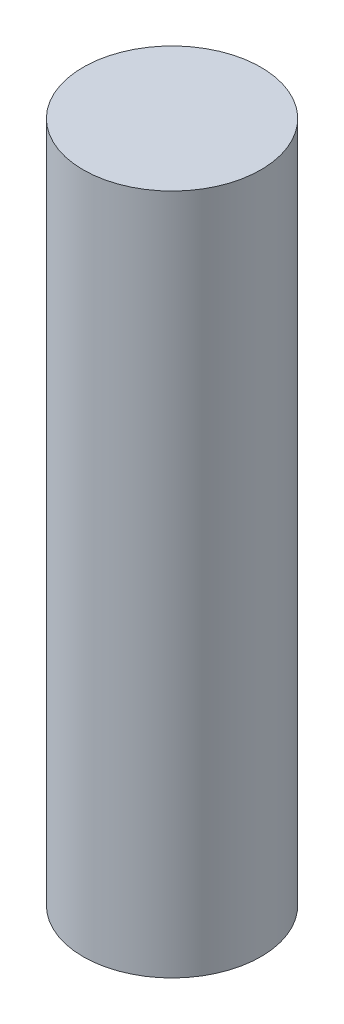
SolidWorks part; units mm, degrees
ref_plane "Front Plane" through (0, 0, 0) normal (0, 0, 1) x (1, 0, 0)
ref_plane "Top Plane" through (0, 0, 0) normal (0, 1, 0) x (1, 0, 0)
ref_plane "Right Plane" through (0, 0, 0) normal (1, 0, 0) x (0, 0, -1)
sketch "Sketch1" plane through (0, 0, 0) normal (0, 1, 0) x (1, 0, 0)
  circle A0 centre (0, 0) radius 1.5
  circle A1 centre (0, 0) radius 1.5 construction
extrude "Boss-Extrude1" add sketch "Sketch1" along normal blind 11.5
